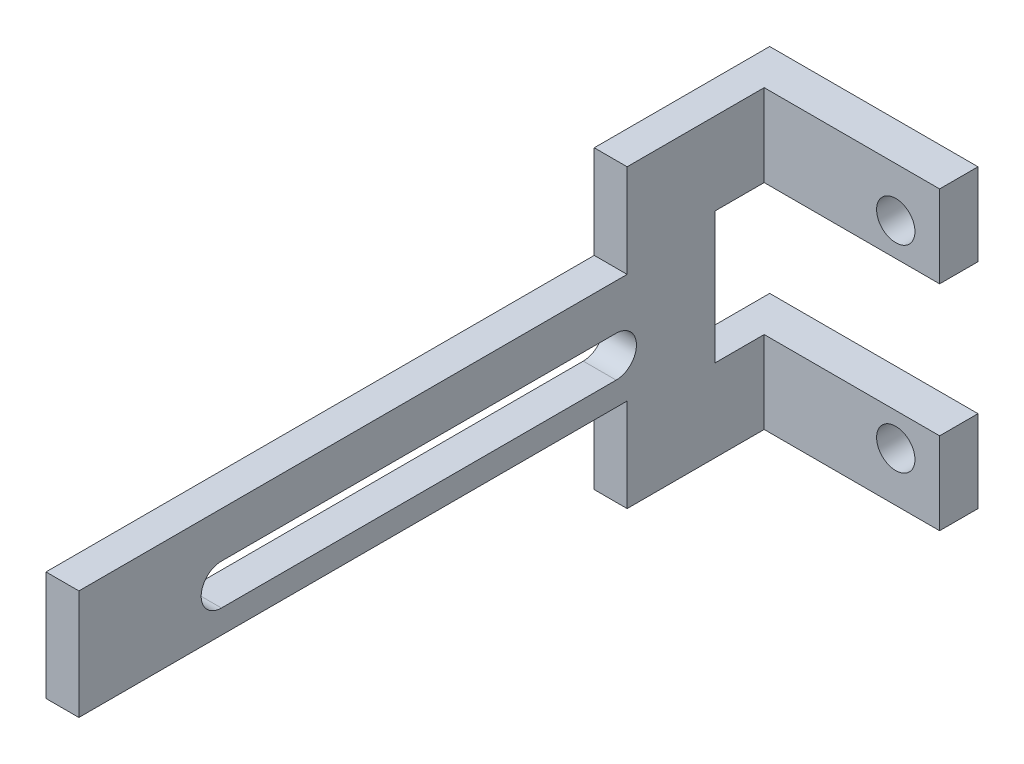
SolidWorks part; units mm, degrees
ref_plane "Front Plane" through (0, 0, 0) normal (1, 0, 0) x (0, 1, 0)
ref_plane "Top Plane" through (0, 0, 0) normal (0, 0, 1) x (0, 1, 0)
ref_plane "Right Plane" through (0, 0, 0) normal (0, 1, 0) x (-1, 0, 0)
sketch "Sketch2" plane through (0, 0, 0) normal (1, 0, 0) x (0, 1, 0)
  line L0 (55, 0) -> (-55, 0) construction
  line L1 (-5, 0) -> (5, 0) construction
  line L2 (-5, 0) -> (-5, 66) construction
  line L3 (-5, 66) -> (5, 66)
  line L4 (5, 0) -> (5, 66) construction
  line L5 (-1, 53) -> (-1, 17) construction
  line L6 (-1, 53) -> (-1, 17) construction
  line L7 (0.85, 53) -> (0.85, 17)
  line L8 (-2.85, 53) -> (-2.85, 17)
  line L9 (-5, 66) -> (-5, 16)
  line L10 (-13.5, 16) -> (-5, 16)
  line L11 (-13.5, 16) -> (-13.5, 0)
  line L12 (-13.5, 0) -> (13.5, 0)
  line L13 (13.5, 16) -> (13.5, 0)
  line L14 (5, 66) -> (5, 16)
  line L15 (5, 16) -> (13.5, 16)
  arc A0 (0.85, 53) -> (-2.85, 53) centre (-1, 53) ccw
  arc A1 (-2.85, 17) -> (0.85, 17) centre (-1, 17) ccw
  point P6 (0, 0)
  point P10 (-1, 35)
  dimension "D3" = 1.85
  dimension "D6" = 1
  dimension "D1" = 10
  dimension "D2" = 50
  dimension "D4" = 36
  dimension "D5" = 6
  dimension "D7" = 27
  dimension "D8" = 16
  dimension "D9" = 13.5
extrude "Boss-Extrude1" add sketch "Sketch2" along normal blind 3
sketch "Sketch3" plane through (3, 0, 0) normal (1, 0, 0) x (0, 1, 0)
  line L7 (-13.5, 16) -> (-13.5, 0) construction
  line L8 (-13.5, 3.5) -> (13.5, 3.5)
  line L9 (-13.5, 3.5) -> (-13.5, 0)
  line L10 (-13.5, 0) -> (13.5, 0)
  line L11 (13.5, 3.5) -> (13.5, 0)
  line L12 (55, 0) -> (-55, 0) construction
  line L13 (13.5, 0) -> (13.5, 16) construction
  dimension "D1" = 3.5
extrude "Boss-Extrude2" add sketch "Sketch3" along normal blind 16
sketch "Sketch4" plane through (0, 0, 3.5) normal (0, 0, 1) x (1, 0, 0)
  line L0 (15, 13.5) -> (15, -13.5) construction
  line L3 (3, 13.5) -> (3, -13.5) construction
  circle A0 centre (15, 9) radius 1.75
  circle A1 centre (15, -9) radius 1.75
  dimension "D4" = 3.5
  dimension "D5" = 3.5
  dimension "D1" = 12
  dimension "D2" = 18
  dimension "D3" = 9
extrude "Cut-Extrude1" cut sketch "Sketch4" against normal blind 10
sketch "Sketch5" plane through (19, 0, 0) normal (1, 0, 0) x (0, 1, 0)
  line L0 (55, 0) -> (-55, 0) construction
  line L1 (-6, 0) -> (6, 0)
  line L2 (-6, 0) -> (-6, 8)
  line L3 (-6, 8) -> (6, 8)
  line L4 (6, 0) -> (6, 8)
  dimension "D1" = 12
  dimension "D2" = 6
  dimension "D3" = 8
extrude "Cut-Extrude2" cut sketch "Sketch5" against normal blind 21
